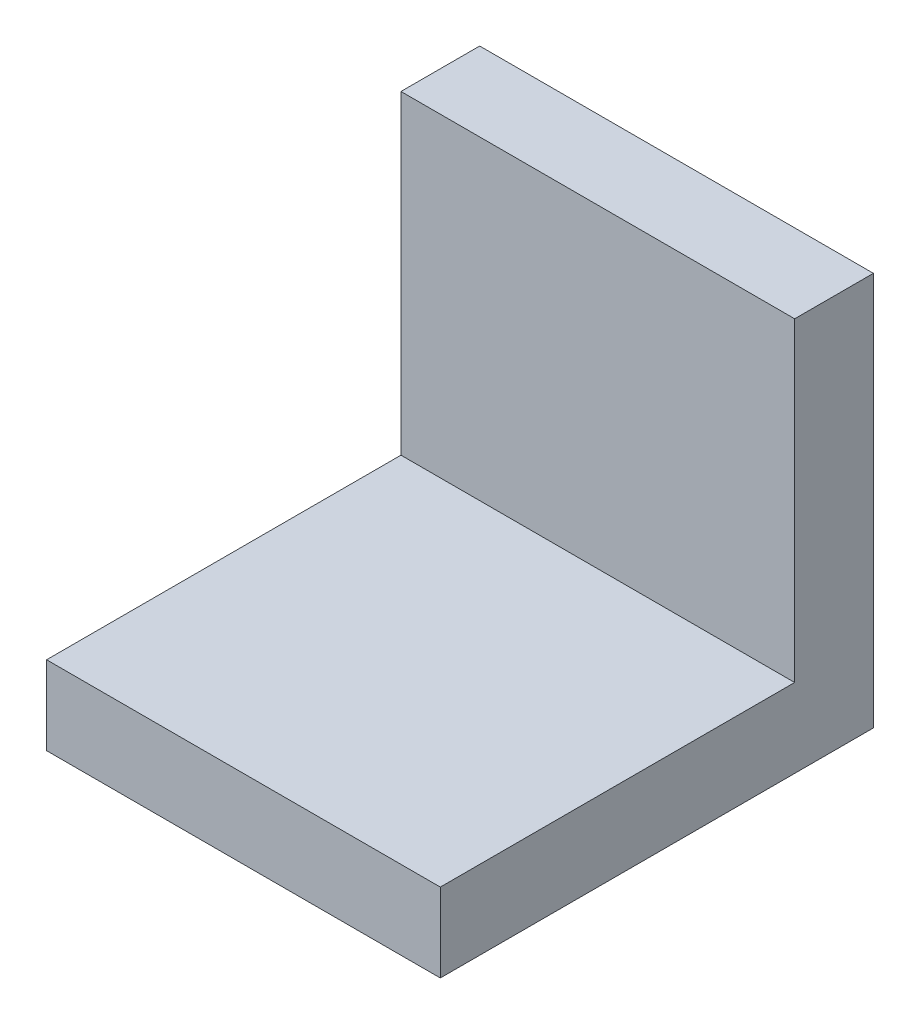
SolidWorks part; units mm, degrees
ref_plane "Plan de face" through (0, 0, 0) normal (0, 0, 1) x (1, 0, 0)
ref_plane "Plan de dessus" through (0, 0, 0) normal (0, 1, 0) x (1, 0, 0)
ref_plane "Plan de droite" through (0, 0, 0) normal (1, 0, 0) x (0, 0, -1)
sketch "Esquisse1" plane through (0, 0, 0) normal (1, 0, 0) x (0, 0, -1)
  line L0 (-27.5, 0) -> (27.5, 0)
  line L1 (27.5, 0) -> (27.5, 50)
  line L2 (27.5, 50) -> (17.5, 50)
  line L3 (17.5, 50) -> (17.5, 10)
  line L4 (17.5, 10) -> (-27.5, 10)
  line L5 (-27.5, 10) -> (-27.5, 0)
  point P4 (0, 0)
  dimension "D1" = 10
  dimension "D2" = 10
  dimension "D3" = 40
  dimension "D4" = 55
extrude "Boss.-Extru.1" add sketch "Esquisse1" along normal mid plane 50
